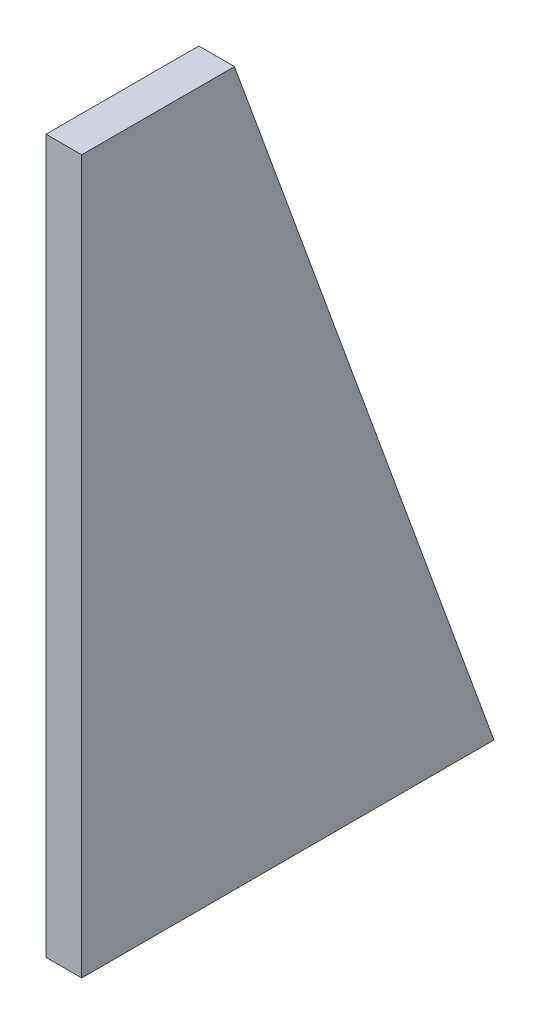
SolidWorks part; units mm, degrees
ref_plane "Front Plane" through (0, 0, 0) normal (0, 0, 1) x (1, 0, 0)
ref_plane "Top Plane" through (0, 0, 0) normal (0, 1, 0) x (1, 0, 0)
ref_plane "Right Plane" through (0, 0, 0) normal (1, 0, 0) x (0, 0, -1)
sketch "Sketch1" plane through (0, 0, 0) normal (1, 0, 0) x (0, 0, -1)
  line L1 (-50, 50) -> (50, 50)
  line L2 (-50, 50) -> (-50, -50)
  line L3 (-50, -50) -> (50, -50)
  line L4 (50, 50) -> (50, -50)
  line L5 (-50, 50) -> (50, -50) construction
  line L6 (-50, -50) -> (50, 50) construction
  point P0 (0, 0)
  dimension "D1" = 100
  dimension "D2" = 100
extrude "Boss-Extrude1" add sketch "Sketch1" along normal blind 10
sketch "Sketch2" plane through (0, 0, 0) normal (-1, 0, 0) x (0, 0, 1)
  line L0 (-50, -50) -> (-50, 50)
  line L1 (-50, 50) -> (50, 50)
  line L2 (50, 50) -> (50, -50)
  line L3 (50, -50) -> (-50, -50)
  line L4 (38.897, 50) -> (50, 50)
  line L5 (0, -50) -> (2.5, -50)
  line L6 (0, -50) -> (-2.5, -50)
  line L7 (36.397, 50) -> (38.897, 50)
  line L8 (36.397, 50) -> (33.897, 50)
  line L9 (33.897, 50) -> (-2.5, -50)
  line L10 (38.897, 50) -> (2.5, -50)
  line L11 (50, -50) -> (50, 50)
  line L12 (50, -50) -> (2.5, -50)
  line L13 (2.5, -50) -> (38.897, 50)
  line L14 (7.1985, -51.7101) -> (7.8209, -50)
  line L15 (45, 45) -> (45, -45)
  line L16 (45, -45) -> (9.6407, -45)
  line L17 (9.6407, -45) -> (42.3981, 45)
  line L18 (50, -45) -> (-45, -45) construction
  line L19 (7.1985, -51.7101) -> (43.5955, 48.2899) construction
  line L20 (45, 50) -> (45, -50) construction
  line L21 (42.3981, 45) -> (45, 45)
  line L22 (-45, 45) -> (50, 45) construction
  line L23 (-0.6801, -45) -> (4.3199, -45)
  line L24 (-45, -45) -> (-45, 45) construction
  line M19 (50, 50) -> (-50, 50)
  dimension "D1" = 5
  dimension "D2" = 2.5
  dimension "D3" = 2.5
  dimension "D4" = 70
extrude "Cut-Extrude2" cut sketch "Sketch2" against normal blind 5 contours L10 L1 L9 L3 M19
sketch "Sketch3" plane through (0, -50, 0) normal (0, -1, 0) x (1, 0, 0)
  line L0 (10, 50) -> (10, -50)
sketch "Sketch5" plane through (0, 0, 0) normal (-1, 0, 0) x (0, 0, 1)
  line L0 (-50, 50) -> (33.897, 50)
  line L2 (-2.5, -50) -> (-50, -50)
  line L3 (-50, -50) -> (-50, 50)
  line L4 (33.897, 50) -> (-2.5, -50)
  line L6 (26.7563, 45) -> (-6.001, -45)
  line L9 (26.7563, 45) -> (28.5761, 50)
  line L10 (-6.001, -45) -> (-7.8209, -50)
  line L12 (-6.001, -45) -> (-45, -45) construction
  line L13 (-45, -45) -> (-45, 45) construction
  line L14 (-45, 45) -> (26.7563, 45) construction
  line M18 (-50, 50) -> (-50, -50)
  line M19 (-50, -50) -> (50, -50)
  dimension "D1" = 5
  dimension "D2" = 180
  dimension "D3" = 180
extrude "Cut-Extrude4" cut sketch "Sketch5" against normal blind 10 contours L10 L6 L9 L0 M18 M19
sketch "Sketch7" plane through (0, 0, 0) normal (-1, 0, 0) x (0, 0, 1)
  line L0 (28.5761, 50) -> (50, 50)
  line L1 (50, 50) -> (50, -50)
  line L2 (50, -50) -> (-7.8209, -50)
  line L3 (-7.8209, -50) -> (28.5761, 50)
extrude "Cut-Extrude5" cut sketch "Sketch7" against normal blind 5
sketch "Sketch8" plane through (0, -50, 0) normal (0, -1, 0) x (1, 0, 0)
  line L0 (5, 50) -> (10, 50)
  line L1 (10, 50) -> (10, -7.8209)
  line L2 (10, -7.8209) -> (5, -7.8209)
  line L3 (5, -7.8209) -> (5, 50)
  line L4 (5, 50) -> (5, 0)
  line L5 (5, 0) -> (10, 0)
  line L6 (10, 0) -> (10, 50)
  line L7 (10, 50) -> (10, 45)
  line L8 (10, 45) -> (5, 45)
  line L9 (5, 45) -> (5, 50)
  line L10 (7.5, 45) -> (7.5, 47.5)
  line L11 (10, 50) -> (9, 50)
  line L12 (10, 50) -> (10, 49)
  line L13 (10, 0) -> (10, 50)
  line L14 (6, 46) -> (9, 46)
  line L15 (6, 46) -> (6, 49)
  line L16 (6, 49) -> (9, 49)
  line L17 (9, 46) -> (9, 49)
  line L18 (6, 46) -> (9, 49) construction
  line L19 (6, 49) -> (9, 46) construction
  line L20 (10, 25) -> (7.5, 25)
  line L21 (6, 1) -> (9, 1)
  line L22 (9, 4) -> (9, 1)
  line L23 (6, 4) -> (9, 4)
  line L24 (6, 4) -> (6, 1)
extrude "Cut-Extrude6" cut sketch "Sketch8" against normal blind 5
sketch "Sketch9" plane through (10, 0, 0) normal (1, 0, 0) x (0, 0, -1)
  line L0 (-50, 50) -> (-33.897, 50)
  line L1 (-33.897, 50) -> (2.5, -50)
  line L2 (2.5, -50) -> (-50, -50)
  line L3 (-50, -50) -> (-50, 50)
  line L4 (-45, -45) -> (-45, 45)
  line L5 (-45, 45) -> (-37.3981, 45)
  line L6 (-37.3981, 45) -> (-4.6407, -45)
  line L7 (-4.6407, -45) -> (-45, -45)
  dimension "D1" = 5
sketch "Sketch11" plane through (10, 0, 0) normal (1, 0, 0) x (0, 0, -1)
  line L0 (-50, -50) -> (7.8209, -50)
sketch "Sketch12" plane through (5, 0, 0) normal (-1, 0, 0) x (0, 0, 1)
  line L0 (50, -50) -> (-7.8209, -50)
  line L1 (-7.8209, -50) -> (28.5761, 50)
  line L2 (28.5761, 50) -> (50, 50)
  line L3 (50, 50) -> (50, -50)
  dimension "D1" = 21.4239
